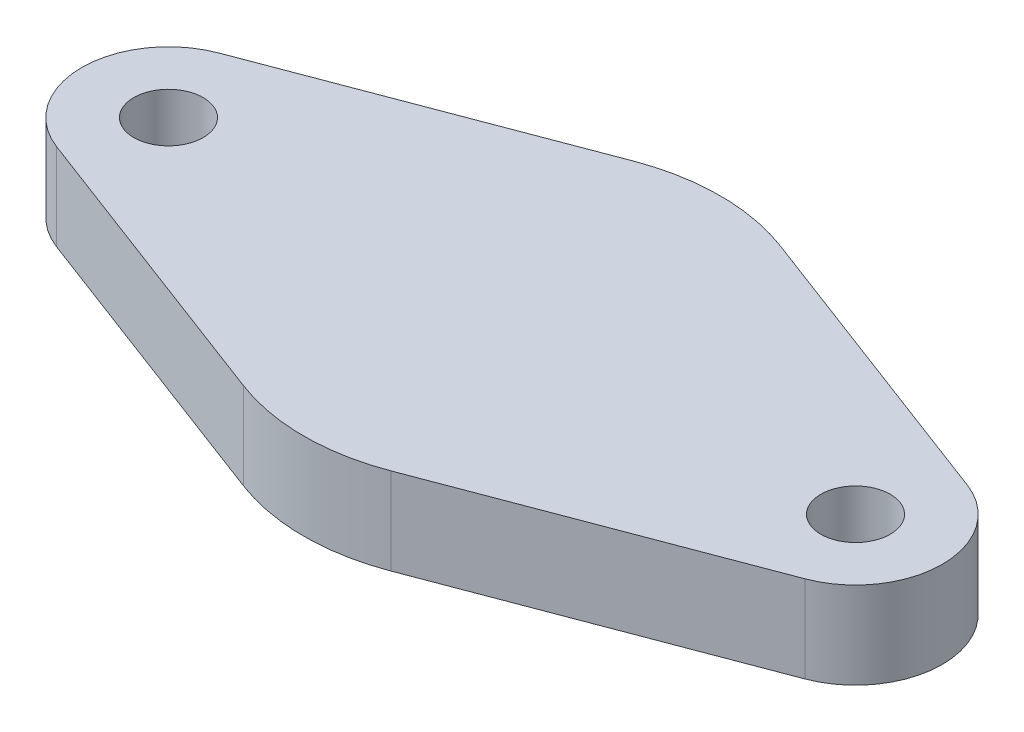
SolidWorks part; units mm, degrees
ref_plane "Front Plane" through (0, 0, 0) normal (0, 0, 1) x (1, 0, 0)
ref_plane "Top Plane" through (0, 0, 0) normal (0, 1, 0) x (1, 0, 0)
ref_plane "Right Plane" through (0, 0, 0) normal (1, 0, 0) x (0, 0, -1)
sketch "Sketch1" plane through (0, 0, 0) normal (0, 1, 0) x (1, 0, 0)
  line L2 (-21.5677, 4.6771) -> (-4.2424, 11.2251)
  line L3 (21.5677, -4.6771) -> (4.2424, -11.2251)
  line L4 (-21.5677, -4.6771) -> (-4.2424, -11.2251)
  line L5 (21.5677, 4.6771) -> (4.2424, 11.2251)
  circle A0 centre (-19.8, 0) radius 2
  arc A2 (-21.5677, 4.6771) -> (-21.5677, -4.6771) centre (-19.8, 0) ccw
  arc A3 (-4.2424, -11.2251) -> (4.2424, -11.2251) centre (0, 0) ccw
  arc A4 (4.2424, 11.2251) -> (-4.2424, 11.2251) centre (0, 0) ccw
  arc A5 (21.5677, 4.6771) -> (21.5677, -4.6771) centre (19.8, 0) cw
  circle A6 centre (19.8, 0) radius 2
extrude "Boss-Extrude2" add sketch "Sketch1" along normal blind 5
